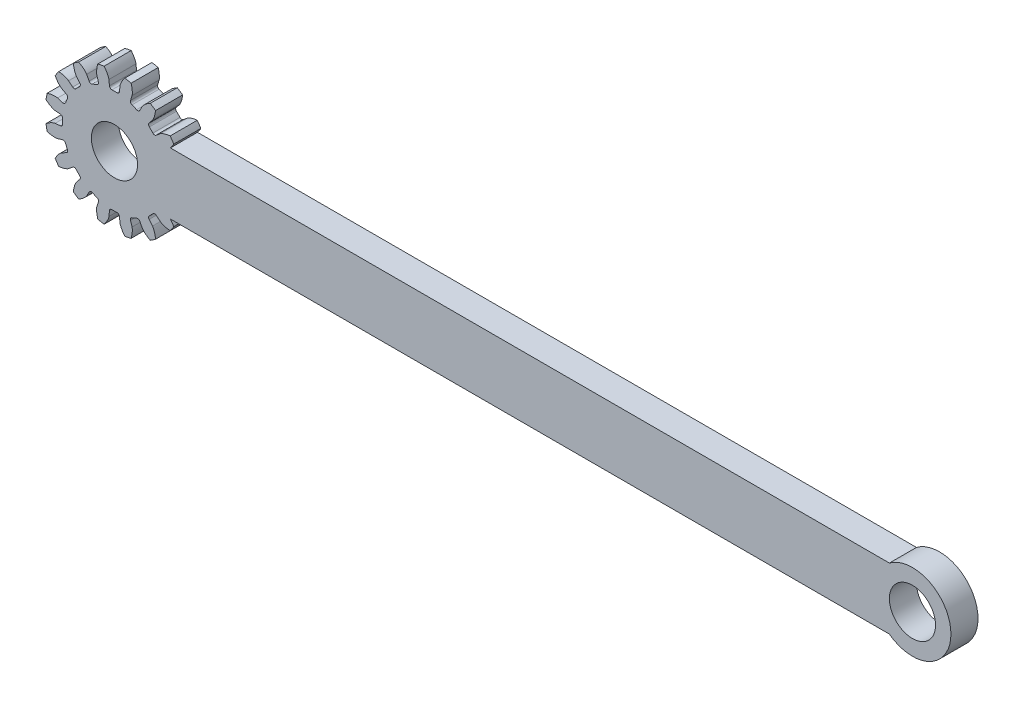
SolidWorks part; units mm, degrees
ref_plane "Front Plane" through (0, 0, 0) normal (0, 0, 1) x (1, 0, 0)
ref_plane "Top Plane" through (0, 0, 0) normal (0, 1, 0) x (1, 0, 0)
ref_plane "Right Plane" through (0, 0, 0) normal (1, 0, 0) x (0, 0, -1)
sketch "Sketch1" plane through (0, 0, 0) normal (0, 0, 1) x (1, 0, 0)
  line L1 (12.7988, -6.35) -> (159.9195, -6.35)
  line L3 (12.7988, 6.35) -> (159.9195, 6.35)
  arc A1 (159.9195, -6.35) -> (159.9195, 6.35) centre (164.682, 0) ccw
  arc A2 (12.7988, 6.35) -> (12.7988, -6.35) centre (0, 0) ccw
  dimension "D4" = 15.875
  dimension "D2" = 28.575
  dimension "D1" = 12.7
extrude "Boss-Extrude1" add sketch "Sketch1" along normal blind 5.588
sketch "Sketch3" plane through (0, 0, 5.588) normal (0, 0, 1) x (1, 0, 0)
  line L0 (0, 0) -> (10.6697, 0.9912) construction
  line L1 (10.6697, 0.9912) -> (12.2428, 1.1373)
  line L2 (0, 0) -> (10.6697, -0.9912) construction
  line L3 (10.6697, -0.9912) -> (12.2428, -1.1373)
  circle A0 centre (0, 0) radius 14.2875 construction
  circle A1 centre (0, 0) radius 12.7 construction
  circle A2 centre (0, 0) radius 12.2955 construction
  circle A3 centre (0, 0) radius 10.7156 construction
  arc A6 (10.6697, 0.9912) -> (10.6697, -0.9912) centre (0, 0) cw
  arc A7 (14.1269, 2.1361) -> (14.1269, -2.1361) centre (0, 0) cw
  spline S0 degree 4 poles (12.2428, 1.1373) (12.2459, 1.1376) (12.2548, 1.1387) (12.2715, 1.1412) (12.2987, 1.1459) (12.3332, 1.153) (12.3777, 1.1633) (12.4298, 1.1769) (12.4868, 1.1934) (12.5485, 1.213) (12.6098, 1.234) (12.6707, 1.2564) (12.7311, 1.2799) (12.8039, 1.3098) (12.8907, 1.3478) (12.9915, 1.395) (13.1049, 1.452) (13.2195, 1.5138) (13.3315, 1.5775) (13.4435, 1.6454) (13.5513, 1.7135) (13.662, 1.7877) (13.7637, 1.858) (13.8763, 1.9405) (13.9669, 2.0083) (14.0849, 2.1017) (14.1541, 2.158) (14.2346, 2.2254) (14.2701, 2.256) (14.292, 2.2749) knots 0 0 0 0 0 0.005377 0.015084 0.028532 0.04661 0.064855 0.092111 0.119476 0.146842 0.174209 0.201575 0.228941 0.256307 0.307035 0.361767 0.4165 0.471232 0.525964 0.580697 0.635429 0.690161 0.744894 0.799626 0.854358 0.909091 0.954545 1 1 1 1 1 construction
  spline S1 degree 4 poles (12.2428, 1.1373) (12.2459, 1.1376) (12.2548, 1.1387) (12.2715, 1.1412) (12.2987, 1.1459) (12.3332, 1.153) (12.3777, 1.1633) (12.4298, 1.1769) (12.4868, 1.1934) (12.5485, 1.213) (12.6098, 1.234) (12.6707, 1.2564) (12.7311, 1.2799) (12.8039, 1.3098) (12.8907, 1.3478) (12.9915, 1.395) (13.1049, 1.452) (13.2195, 1.5138) (13.3315, 1.5775) (13.4435, 1.6454) (13.5513, 1.7135) (13.662, 1.7877) (13.7637, 1.858) (13.8763, 1.9405) (13.9669, 2.0083) (14.0593, 2.0814) (14.1041, 2.1175) (14.1269, 2.1361) knots 0 0 0 0 0 0.005377 0.015084 0.028532 0.04661 0.064855 0.092111 0.119476 0.146842 0.174209 0.201575 0.228941 0.256307 0.307035 0.361767 0.4165 0.471232 0.525964 0.580697 0.635429 0.690161 0.744894 0.799626 0.854358 0.909091 0.909091 0.909091 0.909091 0.909091
  spline S2 degree 4 poles (12.2428, -1.1373) (12.2459, -1.1376) (12.2548, -1.1387) (12.2715, -1.1412) (12.2987, -1.1459) (12.3332, -1.153) (12.3777, -1.1633) (12.4298, -1.1769) (12.4868, -1.1934) (12.5485, -1.213) (12.6098, -1.234) (12.6707, -1.2564) (12.7311, -1.2799) (12.8039, -1.3098) (12.8907, -1.3478) (12.9915, -1.395) (13.1049, -1.452) (13.2195, -1.5138) (13.3315, -1.5775) (13.4435, -1.6454) (13.5513, -1.7135) (13.662, -1.7877) (13.7637, -1.858) (13.8763, -1.9405) (13.9669, -2.0083) (14.0849, -2.1017) (14.1541, -2.158) (14.2346, -2.2254) (14.2701, -2.256) (14.292, -2.2749) knots 0 0 0 0 0 0.005377 0.015084 0.028532 0.04661 0.064855 0.092111 0.119476 0.146842 0.174209 0.201575 0.228941 0.256307 0.307035 0.361767 0.4165 0.471232 0.525964 0.580697 0.635429 0.690161 0.744894 0.799626 0.854358 0.909091 0.954545 1 1 1 1 1 construction
  spline S3 degree 4 poles (12.2428, -1.1373) (12.2459, -1.1376) (12.2548, -1.1387) (12.2715, -1.1412) (12.2987, -1.1459) (12.3332, -1.153) (12.3777, -1.1633) (12.4298, -1.1769) (12.4868, -1.1934) (12.5485, -1.213) (12.6098, -1.234) (12.6707, -1.2564) (12.7311, -1.2799) (12.8039, -1.3098) (12.8907, -1.3478) (12.9915, -1.395) (13.1049, -1.452) (13.2195, -1.5138) (13.3315, -1.5775) (13.4435, -1.6454) (13.5513, -1.7135) (13.662, -1.7877) (13.7637, -1.858) (13.8763, -1.9405) (13.9669, -2.0083) (14.0593, -2.0814) (14.1041, -2.1175) (14.1269, -2.1361) knots 0 0 0 0 0 0.005377 0.015084 0.028532 0.04661 0.064855 0.092111 0.119476 0.146842 0.174209 0.201575 0.228941 0.256307 0.307035 0.361767 0.4165 0.471232 0.525964 0.580697 0.635429 0.690161 0.744894 0.799626 0.854358 0.909091 0.909091 0.909091 0.909091 0.909091
  dimension "D1" = 28.575
  dimension "D2" = 25.4
  dimension "D3" = 24.591
  dimension "D4" = 21.4312
extrude "Cut-Extrude1" cut sketch "Sketch3" against normal through all
fillet "Fillet1" radius 0.4962 2 edges at (10.6697, 0.9912, 2.794) (10.6697, -0.9912, 2.794)
pattern_circular "CirPattern1" count 16 over 360 about axis through (0, 0, 5.588) along (0, 0, 1) of "Fillet1", "Cut-Extrude1"
ref_plane "Plane1" through (10.16, 0, 0) normal (1, 0, 0) x (0, 0, -1)
sketch "Sketch4" plane through (10.16, 0, 0) normal (1, 0, 0) x (0, 0, -1)
  line L6 (0, 6.35) -> (-5.588, 6.35)
  line L8 (0, 6.35) -> (0, -6.35)
  line L9 (0, -6.35) -> (-5.588, -6.35)
  line L10 (-5.588, 6.35) -> (-5.588, -6.35)
  line L11 (0, 6.35) -> (-5.588, -6.35) construction
  line L12 (0, -6.35) -> (-5.588, 6.35) construction
  point P0 (-2.794, 0)
  dimension "D1" = 5.588
  dimension "D2" = 12.7
extrude "Boss-Extrude2" add sketch "Sketch4" against normal mid plane 10.16
sketch "Sketch5" plane through (0, 0, 5.588) normal (0, 0, 1) x (1, 0, 0)
  circle A0 centre (0, 0) radius 4.7625
  circle A1 centre (164.682, 0) radius 4.7625
  dimension "D1" = 9.525
extrude "Cut-Extrude2" cut sketch "Sketch5" against normal through all
equation "\"DiametralPitch\"= 16"
equation "\"NumTeeth\"= 16"
equation "\"PressureAngle\"= 14.5deg"
equation "\"Addendum\"= 1 / \"DiametralPitch\""
equation "\"Dedendum\"= 1.25 / \"DiametralPitch\""
equation "\"WorkingDepth\"= 2 / \"DiametralPitch\""
equation "\"WholeDepth\"= 2.25 / \"DiametralPitch\""
equation "\"Clearance\"= 0.25 / \"DiametralPitch\""
equation "\"ToothThickness\"= 1.5708 / \"DiametralPitch\""
equation "\"CircularPitch\"= pi / \"DiametralPitch\""
equation "\"PitchCircle\"= \"NumTeeth\" / \"DiametralPitch\""
equation "\"OutsideDiameter\"= ( \"NumTeeth\" + 2 ) / \"DiametralPitch\""
equation "\"Fillet\"= \"Clearance\" * cos ( \"PressureAngle\" ) * tan ( ( 90 + \"PressureAngle\" ) / 2 )"
equation "\"AddendumCircle\"= \"PitchCircle\" + ( 2 * \"Addendum\" )"
equation "\"DedendumCircle\"= \"PitchCircle\" - ( 2 * \"Dedendum\" )"
equation "\"BaseCircle\"= \"PitchCircle\" * cos ( \"PressureAngle\" )"
equation "\"PitchAngle\"= 360deg / \"NumTeeth\""
equation "\"Alpha\"= sqr ( \"PitchCircle\" ^ 2 - \"BaseCircle\" ^ 2 ) / \"BaseCircle\" * 180 / PI - \"PressureAngle\""
equation "\"Beta\"= ( \"PitchAngle\" / 4 - \"Alpha\" )"
equation "\"Phi\"= sqr ( ( \"AddendumCircle\" / 2 ) ^ 2 - ( \"BaseCircle\" / 2 ) ^ 2 ) / ( \"BaseCircle\" / 2 )"
equation "\"D2@Sketch1\"= \"OutsideDiameter\""
equation "\"D1@Sketch3\"=\"OutsideDiameter\""
equation "\"D2@Sketch3\"=\"PitchCircle\""
equation "\"D3@Sketch3\"=\"BaseCircle\""
equation "\"D4@Sketch3\"=\"DedendumCircle\""
equation "\"D1@Fillet1\"=\"Fillet\""
equation "\"D1@CirPattern1\"=\"NumTeeth\""
